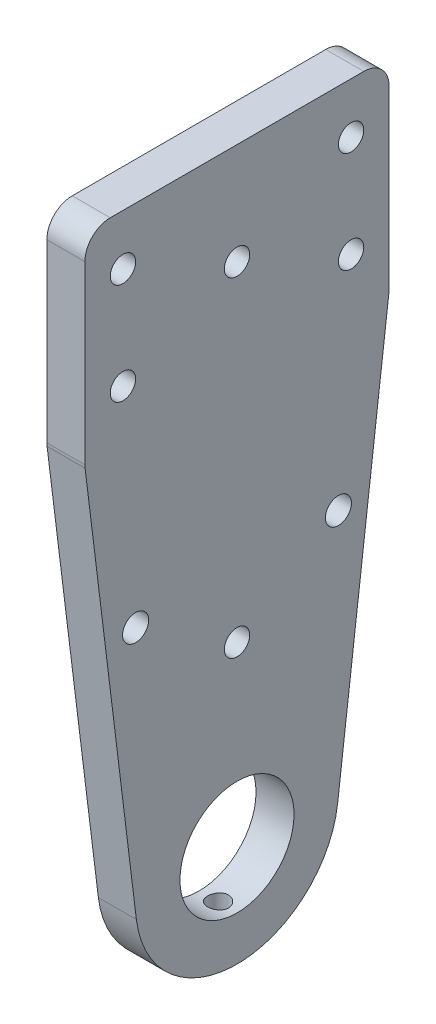
SolidWorks part; units mm, degrees
ref_plane "Front Plane" through (0, 0, 0) normal (0, 0, 1) x (1, 0, 0)
ref_plane "Top Plane" through (0, 0, 0) normal (0, 1, 0) x (1, 0, 0)
ref_plane "Right Plane" through (0, 0, 0) normal (1, 0, 0) x (0, 0, -1)
sketch "Sketch1" plane through (0, 0, 0) normal (1, 0, 0) x (0, 0, -1)
  line L0 (-42.5256, 632.6525) -> (-55.416, 737.3561)
  line L1 (-55.416, 737.3561) -> (-55.416, 788.1561)
  line L2 (-55.416, 788.1561) -> (20.784, 788.1561)
  line L3 (-17.316, 610.3561) -> (-17.316, 788.1561) construction
  line L4 (20.784, 737.3561) -> (20.784, 788.1561)
  line L5 (7.8937, 632.6525) -> (20.784, 737.3561)
  line L6 (-17.316, 762.7561) -> (-55.416, 762.7561) construction
  line L7 (-36.366, 762.7561) -> (-55.416, 788.1561) construction
  circle A1 centre (-17.316, 635.7561) radius 14.2875
  arc A2 (7.8937, 632.6525) -> (-42.5256, 632.6525) centre (-17.316, 635.7561) cw
  circle A3 centre (-45.891, 775.4561) radius 3.175
  circle A4 centre (-17.316, 762.7561) radius 3.175
  circle A5 centre (-45.891, 750.0561) radius 3.175
  circle A6 centre (11.259, 750.0561) radius 3.175
  circle A7 centre (11.259, 775.4561) radius 3.175
  circle A9 centre (8.084, 696.0811) radius 3.2639
  circle A10 centre (-17.316, 680.2061) radius 3.175
  circle A11 centre (-42.716, 696.0811) radius 3.2639
  circle A24 centre (-17.316, 635.7561) radius 12.7 construction
  circle A25 centre (-17.316, 635.7561) radius 12.7 construction
  point P11 (-17.316, 762.7561)
  dimension "D1" = 25.4
  dimension "D5" = 6.35
  dimension "D6" = 6.35
  dimension "D7" = 6.5278
  dimension "D12" = 28.575
  dimension "D2" = 63.5
  dimension "D3" = 76.2
  dimension "D4" = 50.8
  dimension "D8" = 127
  dimension "D9" = 25.4
  dimension "D10" = 44.45
extrude "Boss-Extrude1" add sketch "Sketch1" against normal blind 9.525 from surface at -38.1
ref_plane "Plane1" through (0, 610.3561, 0) normal (0, -1, 0) x (-1, 0, 0)
sketch "Sketch2" plane through (0, 610.3561, 0) normal (0, -1, 0) x (-1, 0, 0)
  line L4 (47.625, -17.316) -> (38.1, -17.316)
  line L5 (47.625, -17.316) -> (38.1, -17.316) construction
  circle A0 centre (42.8625, -17.316) radius 2.6035
  dimension "D1" = 5.207
extrude "Cut-Extrude1" cut sketch "Sketch2" against normal up to surface (11.3517 mm away)
ref_plane "mid" through (0, 0, 17.316) normal (0, 0, 1) x (1, 0, 0)
fillet "Fillet1" radius 6.35 4 edges at (-42.8625, 737.3561, -20.784) (-42.8625, 788.1561, -20.784) (-42.8625, 737.3561, 55.416) (-42.8625, 788.1561, 55.416)
